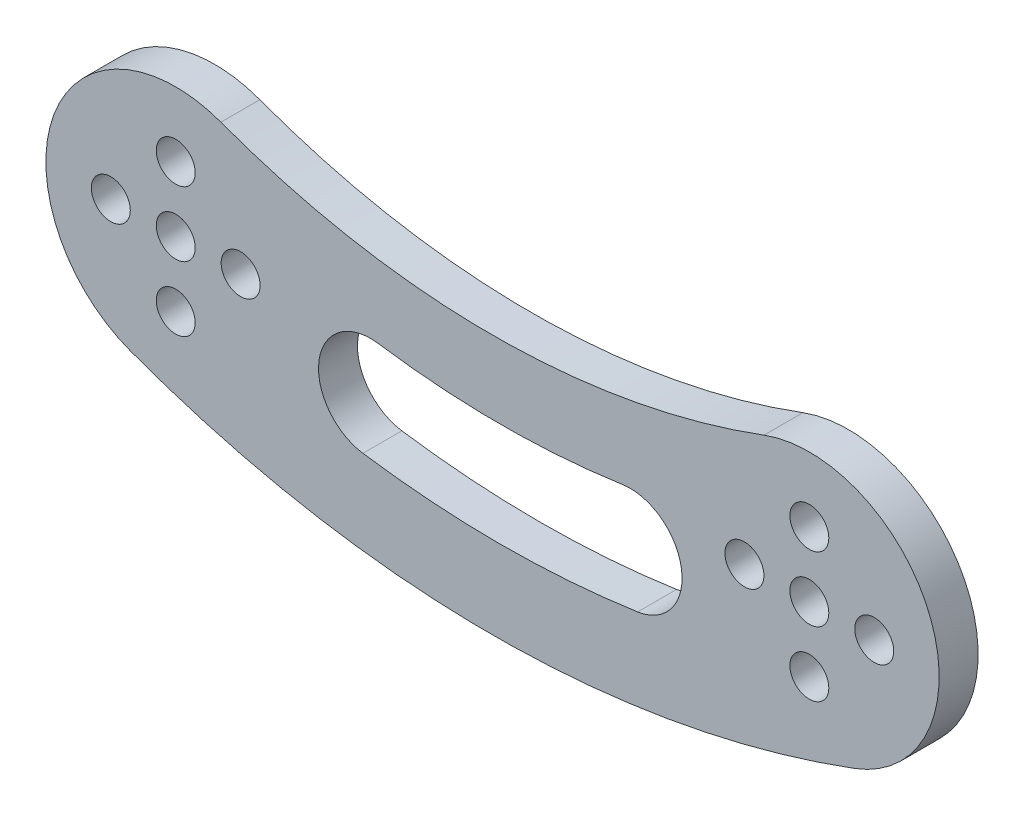
SolidWorks part; units mm, degrees
ref_plane "Front" through (0, 0, 0) normal (0, 0, 1) x (1, 0, 0)
ref_plane "Top" through (0, 0, 0) normal (0, 1, 0) x (1, 0, 0)
ref_plane "Right" through (0, 0, 0) normal (1, 0, 0) x (0, 0, -1)
sketch "Çizim3" plane through (0, 0, 0) normal (0, 0, 1) x (1, 0, 0)
  line L0 (-25, 0) -> (-18.5, 0) construction
  line L1 (17.3033, 0) -> (25, 0) construction
  arc A0 (-21.5228, 9.376) -> (-28.4772, -9.376) centre (-25, 0) ccw
  arc A1 (27.2973, -9.324) -> (20.308, 9.415) centre (23.8027, 0.0455) ccw
  circle A2 centre (-25, 0) radius 1.5
  circle A3 centre (-25, 5) radius 1.5
  circle A4 centre (-30, 0) radius 1.5
  circle A5 centre (-20, 0) radius 1.5
  circle A6 centre (-25, -5) radius 1.5
  circle A7 centre (23.8027, 0.0455) radius 1.5
  circle A8 centre (23.8027, 5.0455) radius 1.5
  circle A9 centre (28.8024, 0) radius 1.5
  circle A10 centre (18.8027, 0.0455) radius 1.5
  circle A11 centre (23.8027, -4.9545) radius 1.5
  arc A12 (-21.5228, 9.376) -> (20.308, 9.415) centre (-0.6598, 65.632) ccw
  arc A13 (-28.4772, -9.376) -> (27.2973, -9.324) centre (-0.6598, 65.632) ccw
  arc A14 (-9.4203, 0.6737) -> (9.4203, 0.6737) centre (0, 64.9874) ccw
  arc A15 (-10.5797, -7.2419) -> (10.5797, -7.2419) centre (0, 64.9874) ccw
  arc A16 (-9.4203, 0.6737) -> (-10.5797, -7.2419) centre (-10, -3.2841) ccw
  arc A17 (10.5797, -7.2419) -> (9.4203, 0.6737) centre (10, -3.2841) ccw
  arc A18 (-10, 0.7613) -> (10, 0.7613) centre (0, 64.9874) ccw construction
  arc A19 (-11.2308, -7.1435) -> (11.2308, -7.1435) centre (0, 64.9874) ccw construction
  point P2 (0, 0)
  point P4 (0, 0)
  dimension "D3" = 5
  dimension "D11" = 3
  dimension "D12" = 20
  dimension "D13" = 3
  dimension "D14" = 3
  dimension "D15" = 3
  dimension "D16" = 3
  dimension "D17" = 3
  dimension "D18" = 3
  dimension "D19" = 3
  dimension "D20" = 3
  dimension "D21" = 3
  dimension "D22" = 20
  dimension "D23" = 60
  dimension "D24" = 80
  dimension "D27" = 65
  dimension "D28" = 8
  dimension "D29" = 10
  dimension "D4" = 5
  dimension "D5" = 5
  dimension "D6" = 5
  dimension "D7" = 5
  dimension "D8" = 5
  dimension "D9" = 5
  dimension "D10" = 5
  dimension "D30" = 10
extrude "Yükseklik-Ekstrüzyon1" add sketch "Çizim3" along normal blind 3
